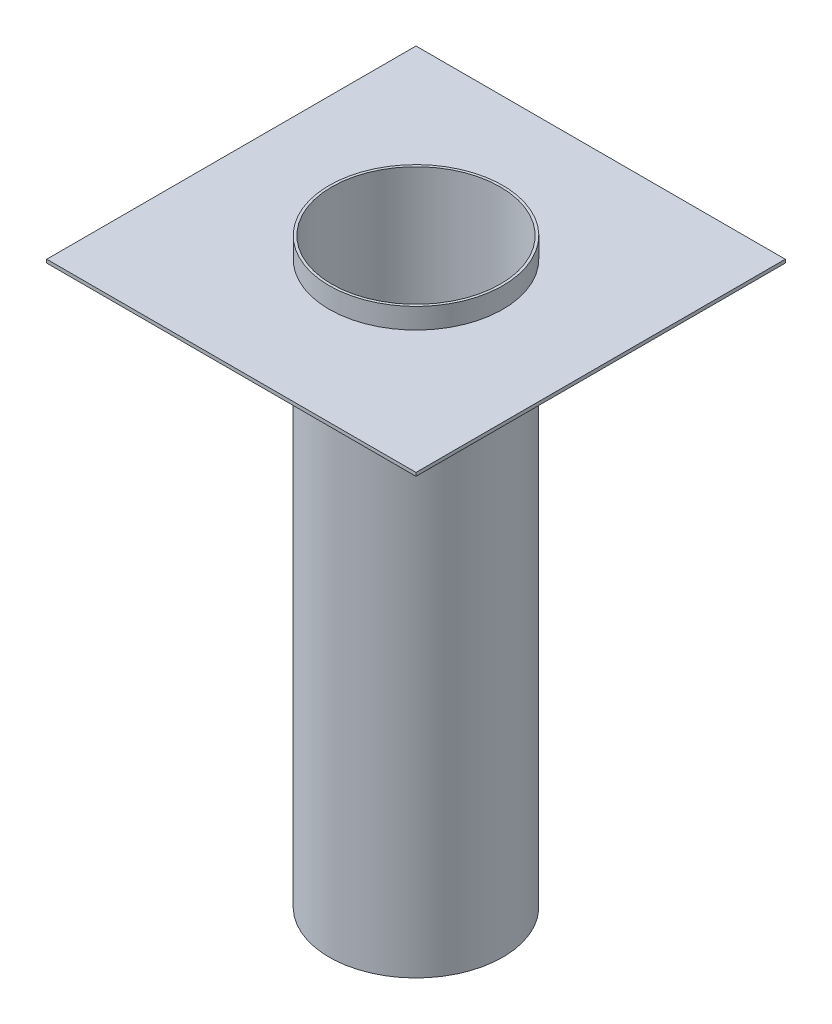
SolidWorks part; units mm, degrees
ref_plane "Front Plane" through (0, 0, 0) normal (0, 0, 1) x (1, 0, 0)
ref_plane "Top Plane" through (0, 0, 0) normal (0, 1, 0) x (1, 0, 0)
ref_plane "Right Plane" through (0, 0, 0) normal (1, 0, 0) x (0, 0, -1)
sketch "Sketch1" plane through (0, 0, 0) normal (0, 1, 0) x (1, 0, 0)
  line L1 (-54, -54) -> (54, -54)
  line L2 (-54, -54) -> (-54, 54)
  line L3 (-54, 54) -> (54, 54)
  line L4 (54, -54) -> (54, 54)
  line L5 (-54, -54) -> (54, 54) construction
  line L6 (-54, 54) -> (54, -54) construction
  point P0 (0, 0)
  dimension "D1" = 108
  dimension "D2" = 108
extrude "Boss-Extrude1" add sketch "Sketch1" along normal blind 170.1
sketch "Sketch2" plane through (0, 170.1, 0) normal (0, 1, 0) x (1, 0, 0)
  circle A0 centre (0, 0) radius 25.4
  dimension "D1" = 50.8
extrude "Cut-Extrude1" cut sketch "Sketch2" against normal blind 6 flip side to cut
sketch "Sketch3" plane through (0, 0, 0) normal (0, -1, 0) x (1, 0, 0)
  circle A0 centre (0, 0) radius 25.4
  dimension "D1" = 50.8
extrude "Cut-Extrude3" cut sketch "Sketch3" against normal blind 163.1 flip side to cut contours A0
sketch "Sketch5" plane through (0, 0, 0) normal (0, -1, 0) x (1, 0, 0)
  circle A0 centre (0, 0) radius 24.65
  dimension "D1" = 49.3
extrude "Cut-Extrude4" cut sketch "Sketch5" against normal through all
